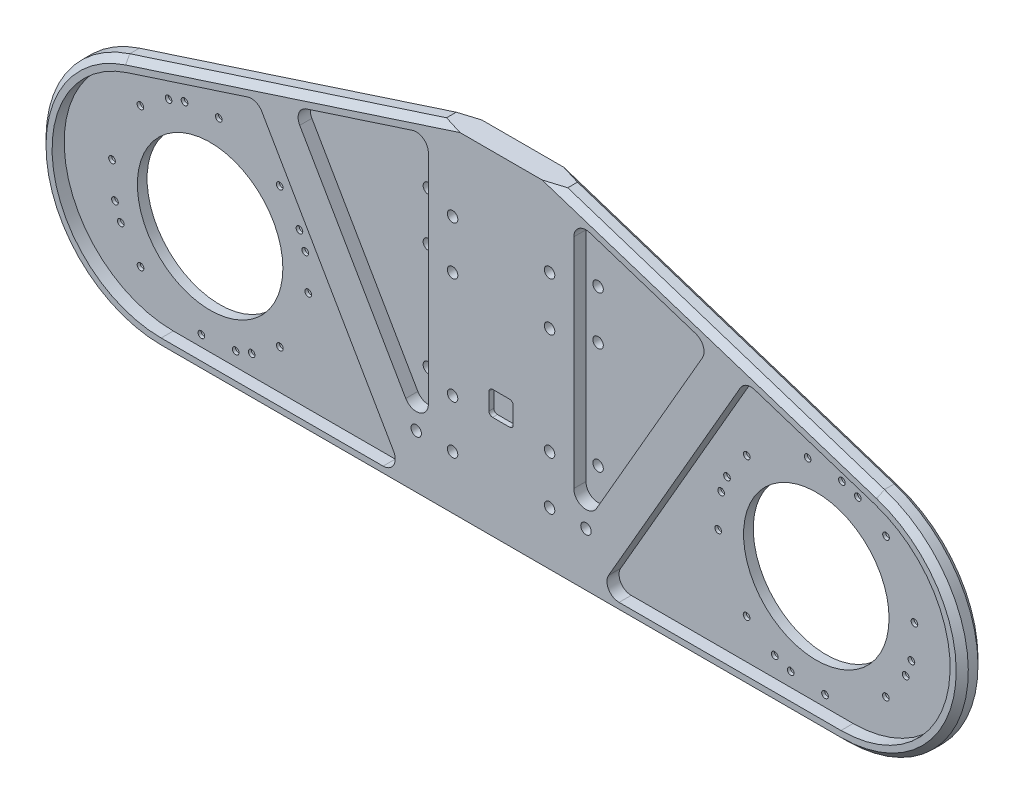
SolidWorks part; units mm, degrees
material "6061 合金"
ref_plane "前视基准面" through (0, 0, 0) normal (0, 0, 1) x (1, 0, 0)
ref_plane "上视基准面" through (0, 0, 0) normal (0, 1, 0) x (1, 0, 0)
ref_plane "右视基准面" through (0, 0, 0) normal (1, 0, 0) x (0, 0, -1)
other "Configuration Table"
sketch "草图1" plane through (0, 0, 0) normal (0, 0, 1) x (1, 0, 0)
  line L0 (0, 0) -> (0, 280) construction
  line L1 (0, 280) -> (861.7514, 0)
  line L3 (861.7514, 0) -> (0, 0)
  line L4 (-50, 352.899) -> (-50, -139.8009) construction
  line L5 (-961.7514, 0) -> (-100, 0)
  line L6 (-100, 280) -> (-961.7514, 0)
  line L7 (-100, 0) -> (-100, 280) construction
  line L8 (-100, 280) -> (0, 280)
  line L9 (0, 0) -> (-100, 0)
  circle A0 centre (200, 100) radius 85 construction
  circle A1 centre (200, 100) radius 60
  circle A2 centre (-300, 100) radius 85 construction
  circle A3 centre (-300, 100) radius 60
  dimension "D1" = 170
  dimension "D4" = 120
  dimension "D2" = 200
  dimension "D3" = 72
  dimension "D5" = 280
  dimension "D6" = 100
  dimension "D7" = 50
extrude "凸台-拉伸1" add sketch "草图1" along normal blind 8 contours L9 L3 L1 L8 L6 L5 A1 A3
fillet "圆角1" radius 100 2 edges at (861.7514, 0, 4) (-961.7514, 0, 4)
sketch "草图2" plane through (0, 0, 8) normal (0, 0, 1) x (1, 0, 0)
  line L0 (10, 266.2362) -> (10, 35.359)
  line L1 (30, 10) -> (230.3762, 10)
  line L2 (10, 266.2362) -> (122.2414, 229.7667)
  line L9 (10, 35.359) -> (122.2414, 229.7667)
  line L10 (30, 10) -> (151.4105, 220.2891)
  line L11 (151.4105, 220.2891) -> (258.1878, 185.5951)
  line L12 (10, 35.359) -> (10, 10) construction
  line L13 (10, 10) -> (30, 10) construction
  line L15 (0, 280) -> (261.2779, 195.1057) construction
  line L16 (230.3762, 0) -> (-330.3762, 0) construction
  line L19 (0, 280) -> (261.2779, 195.1057)
  line L24 (-50, 336.5114) -> (-50, -134.6936) construction
  line L29 (-100, 280) -> (0, 280) construction
  line L30 (230.3762, 0) -> (-330.3762, 0)
  line L31 (0, 280) -> (-100, 280)
  line L39 (-50, 280) -> (-50, 0)
  line L40 (-110, 10) -> (-130, 10) construction
  line L41 (-110, 35.359) -> (-110, 10) construction
  line L42 (-100, 280) -> (-361.2779, 195.1057)
  line L43 (-251.4105, 220.2891) -> (-358.1878, 185.5951)
  line L44 (-130, 10) -> (-251.4105, 220.2891)
  line L45 (-110, 35.359) -> (-222.2414, 229.7667)
  line L46 (-110, 266.2362) -> (-222.2414, 229.7667)
  line L47 (-130, 10) -> (-330.3762, 10)
  line L48 (-110, 266.2362) -> (-110, 35.359)
  arc A0 (230.3762, 10) -> (258.1878, 185.5951) centre (230.3762, 100) ccw
  arc A5 (230.3762, 0) -> (261.2779, 195.1057) centre (230.3762, 100) ccw construction
  arc A7 (230.3762, 0) -> (261.2779, 195.1057) centre (230.3762, 100) ccw
  arc A12 (-330.3762, 0) -> (-361.2779, 195.1057) centre (-330.3762, 100) cw
  arc A13 (-330.3762, 10) -> (-358.1878, 185.5951) centre (-330.3762, 100) cw
  point P33 (-50, 280)
  point P34 (-50, 0)
  line M64 (-100, 280) -> (-361.2779, 195.1057)
  arc M65 (-361.2779, 195.1057) -> (-330.3762, 0) centre (-330.3762, 100) ccw
  line M66 (-330.3762, 0) -> (230.3762, 0)
  arc M67 (230.3762, 0) -> (261.2779, 195.1057) centre (230.3762, 100) ccw
  line M68 (261.2779, 195.1057) -> (0, 280)
  line M69 (0, 280) -> (-100, 280)
  dimension "D4" = 10
  dimension "D2" = 10
  dimension "D3" = 10
  dimension "D6" = 30
  dimension "D7" = 60
  dimension "D8" = 20
  dimension "D1" = 10
extrude "凸台-拉伸2" add sketch "草图2" along normal blind 10 contours L39 L31 L46 L48 L45 L47 A13 L43 L44 M64 M65 M66 | L39 L30 A0 L1 L10 L11 L9 L0 L2 M69 M67 M68
fillet "圆角2" radius 10 10 edges at (10, 35.359, 13) (30, 10, 13) (122.2414, 229.7667, 13) (151.4105, 220.2891, 13) (10, 266.2362, 13) (-130, 10, 13) (-251.4105, 220.2891, 13) (-110, 266.2362, 13) (-222.2414, 229.7667, 13) (-110, 35.359, 13)
chamfer "倒角1" distance 5 angle 45 10 edges at (130.639, 237.5528, 0) (-50, 0, 0) (329.1451, 84.3566, 0) (-429.1451, 84.3566, 0) (-50, 0, 18) (329.1451, 84.3566, 18) (130.639, 237.5528, 18) (-230.639, 237.5528, 18) (-429.1451, 84.3566, 18) (-230.639, 237.5528, 0)
sketch "草图3" plane through (0, 0, 0) normal (0, 0, -1) x (-1, 0, 0)
  line L0 (134, 30) -> (100, 30) construction
  line L1 (-34, 236) -> (44, 236) construction
  line L2 (-34, 236) -> (-34, 158) construction
  line L3 (-34, 158) -> (44, 158) construction
  line L5 (-34, 108) -> (44, 108) construction
  line L6 (-34, 108) -> (-34, 30) construction
  line L7 (-34, 30) -> (0, 30) construction
  line L9 (134, 108) -> (134, 30) construction
  line L10 (330.3762, 0) -> (-230.3762, 0) construction
  line L11 (50, 335.2852) -> (50, -119.0767) construction
  line L12 (134, 108) -> (56, 108) construction
  line L13 (134, 158) -> (56, 158) construction
  line L14 (134, 236) -> (134, 158) construction
  line L15 (134, 236) -> (56, 236) construction
  circle A0 centre (-20, 217) radius 4.3
  circle A1 centre (-20, 177) radius 4.3
  circle A2 centre (10, 217) radius 4.3
  circle A3 centre (10, 177) radius 4.3
  circle A4 centre (-20, 89) radius 4.3
  circle A5 centre (10, 89) radius 4.3
  circle A6 centre (-20, 49) radius 4.3
  circle A7 centre (10, 49) radius 4.3
  circle A8 centre (300, 100) radius 60 construction
  circle A9 centre (-200, 100) radius 60 construction
  circle A10 centre (90, 49) radius 4.3
  circle A11 centre (120, 49) radius 4.3
  circle A12 centre (90, 89) radius 4.3
  circle A13 centre (120, 89) radius 4.3
  circle A14 centre (90, 177) radius 4.3
  circle A15 centre (90, 217) radius 4.3
  circle A16 centre (120, 177) radius 4.3
  circle A17 centre (120, 217) radius 4.3
  dimension "D7" = 8.6
  dimension "D16" = 8.6
  dimension "D1" = 78
  dimension "D2" = 78
  dimension "D3" = 30
  dimension "D4" = 78
  dimension "D5" = 30
  dimension "D6" = 50
  dimension "D8" = 19
  dimension "D9" = 19
  dimension "D10" = 19
  dimension "D11" = 19
  dimension "D12" = 14
  dimension "D13" = 14
  dimension "D14" = 40
  dimension "D17" = 19
  dimension "D18" = 19
  dimension "D19" = 19
  dimension "D20" = 19
  dimension "D21" = 14
  dimension "D22" = 14
extrude "切除-拉伸1" cut sketch "草图3" against normal through all both
sketch "草图4" plane through (0, 0, 8) normal (0, 0, 1) x (1, 0, 0)
  line L0 (-50, 330.4726) -> (-50, -61.6586) construction
  arc A0 (259.7806, 158.4465) -> (255.249, 156.3335) centre (257.5148, 157.39) ccw construction
  arc A1 (278.6673, 106.1128) -> (283.1989, 108.2258) centre (280.9331, 107.1693) ccw construction
  arc A2 (276.1928, 77.8292) -> (280.7244, 79.9423) centre (278.4586, 78.8857) ccw construction
  arc A3 (271.409, 64.6857) -> (275.9405, 66.7988) centre (273.6748, 65.7423) ccw construction
  arc A4 (255.1242, 41.4287) -> (259.6558, 43.5418) centre (257.39, 42.4852) ccw construction
  arc A5 (204.9035, 18.0104) -> (209.4351, 20.1235) centre (207.1693, 19.0669) ccw construction
  arc A6 (176.62, 20.4849) -> (181.1515, 22.598) centre (178.8857, 21.5414) ccw construction
  arc A7 (163.4765, 25.2687) -> (168.008, 27.3818) centre (165.7423, 26.3252) ccw construction
  arc A8 (140.2194, 41.5535) -> (144.751, 43.6665) centre (142.4852, 42.61) ccw construction
  arc A9 (121.3327, 93.8872) -> (116.8011, 91.7742) centre (119.0669, 92.8307) ccw construction
  arc A10 (123.8072, 122.1708) -> (119.2756, 120.0577) centre (121.5414, 121.1143) ccw construction
  arc A11 (128.591, 135.3143) -> (124.0595, 133.2012) centre (126.3252, 134.2577) ccw construction
  arc A12 (144.8758, 158.5713) -> (140.3442, 156.4582) centre (142.61, 157.5148) ccw construction
  arc A13 (195.0965, 181.9896) -> (190.5649, 179.8765) centre (192.8307, 180.9331) ccw construction
  arc A14 (223.38, 179.5151) -> (218.8485, 177.402) centre (221.1143, 178.4586) ccw construction
  arc A15 (236.5235, 174.7313) -> (231.992, 172.6182) centre (234.2577, 173.6748) ccw construction
  arc A16 (259.7806, 158.4465) -> (255.249, 156.3335) centre (257.5148, 157.39) ccw construction
  arc A17 (278.6673, 106.1128) -> (283.1989, 108.2258) centre (280.9331, 107.1693) ccw construction
  arc A18 (276.1928, 77.8292) -> (280.7244, 79.9423) centre (278.4586, 78.8857) ccw construction
  arc A19 (271.409, 64.6857) -> (275.9405, 66.7988) centre (273.6748, 65.7423) ccw construction
  arc A20 (255.1242, 41.4287) -> (259.6558, 43.5418) centre (257.39, 42.4852) ccw construction
  arc A21 (204.9035, 18.0104) -> (209.4351, 20.1235) centre (207.1693, 19.0669) ccw construction
  arc A22 (176.62, 20.4849) -> (181.1515, 22.598) centre (178.8857, 21.5414) ccw construction
  arc A23 (163.4765, 25.2687) -> (168.008, 27.3818) centre (165.7423, 26.3252) ccw construction
  arc A24 (140.2194, 41.5535) -> (144.751, 43.6665) centre (142.4852, 42.61) ccw construction
  arc A25 (121.3327, 93.8872) -> (116.8011, 91.7742) centre (119.0669, 92.8307) ccw construction
  arc A26 (123.8072, 122.1708) -> (119.2756, 120.0577) centre (121.5414, 121.1143) ccw construction
  arc A27 (128.591, 135.3143) -> (124.0595, 133.2012) centre (126.3252, 134.2577) ccw construction
  arc A28 (144.8758, 158.5713) -> (140.3442, 156.4582) centre (142.61, 157.5148) ccw construction
  arc A29 (195.0965, 181.9896) -> (190.5649, 179.8765) centre (192.8307, 180.9331) ccw construction
  arc A30 (223.38, 179.5151) -> (218.8485, 177.402) centre (221.1143, 178.4586) ccw construction
  arc A31 (236.5235, 174.7313) -> (231.992, 172.6182) centre (234.2577, 173.6748) ccw construction
  circle A32 centre (257.5148, 157.39) radius 2.75
  circle A33 centre (234.2577, 173.6748) radius 2.75
  circle A34 centre (221.1143, 178.4586) radius 2.75
  circle A35 centre (192.8307, 180.9331) radius 2.75
  circle A36 centre (142.61, 157.5148) radius 2.75
  circle A37 centre (126.3252, 134.2577) radius 2.75
  circle A38 centre (121.5414, 121.1143) radius 2.75
  circle A39 centre (119.0669, 92.8307) radius 2.75
  circle A40 centre (142.4852, 42.61) radius 2.75
  circle A41 centre (165.7423, 26.3252) radius 2.75
  circle A42 centre (178.8857, 21.5414) radius 2.75
  circle A43 centre (207.1693, 19.0669) radius 2.75
  circle A44 centre (257.39, 42.4852) radius 2.75
  circle A45 centre (273.6748, 65.7423) radius 2.75
  circle A46 centre (278.4586, 78.8857) radius 2.75
  circle A47 centre (280.9331, 107.1693) radius 2.75
  circle A48 centre (200, 100) radius 60 construction
  circle A49 centre (-300, 100) radius 60 construction
  arc A50 (-336.5235, 174.7313) -> (-331.992, 172.6182) centre (-334.2577, 173.6748) cw construction
  arc A51 (-323.38, 179.5151) -> (-318.8485, 177.402) centre (-321.1143, 178.4586) cw construction
  arc A52 (-295.0965, 181.9896) -> (-290.5649, 179.8765) centre (-292.8307, 180.9331) cw construction
  arc A53 (-244.8758, 158.5713) -> (-240.3442, 156.4582) centre (-242.61, 157.5148) cw construction
  arc A54 (-228.591, 135.3143) -> (-224.0595, 133.2012) centre (-226.3252, 134.2577) cw construction
  arc A55 (-223.8072, 122.1708) -> (-219.2756, 120.0577) centre (-221.5414, 121.1143) cw construction
  arc A56 (-221.3327, 93.8872) -> (-216.8011, 91.7742) centre (-219.0669, 92.8307) cw construction
  arc A57 (-240.2194, 41.5535) -> (-244.751, 43.6665) centre (-242.4852, 42.61) cw construction
  arc A58 (-263.4765, 25.2687) -> (-268.008, 27.3818) centre (-265.7423, 26.3252) cw construction
  arc A59 (-276.62, 20.4849) -> (-281.1515, 22.598) centre (-278.8857, 21.5414) cw construction
  arc A60 (-304.9035, 18.0104) -> (-309.4351, 20.1235) centre (-307.1693, 19.0669) cw construction
  arc A61 (-355.1242, 41.4287) -> (-359.6558, 43.5418) centre (-357.39, 42.4852) cw construction
  arc A62 (-371.409, 64.6857) -> (-375.9405, 66.7988) centre (-373.6748, 65.7423) cw construction
  arc A63 (-376.1928, 77.8292) -> (-380.7244, 79.9423) centre (-378.4586, 78.8857) cw construction
  arc A64 (-378.6673, 106.1128) -> (-383.1989, 108.2258) centre (-380.9331, 107.1693) cw construction
  arc A65 (-359.7806, 158.4465) -> (-355.249, 156.3335) centre (-357.5148, 157.39) cw construction
  circle A66 centre (-380.9331, 107.1693) radius 2.75
  circle A67 centre (-378.4586, 78.8857) radius 2.75
  circle A68 centre (-373.6748, 65.7423) radius 2.75
  circle A69 centre (-357.39, 42.4852) radius 2.75
  circle A70 centre (-307.1693, 19.0669) radius 2.75
  circle A71 centre (-278.8857, 21.5414) radius 2.75
  circle A72 centre (-265.7423, 26.3252) radius 2.75
  circle A73 centre (-242.4852, 42.61) radius 2.75
  circle A74 centre (-219.0669, 92.8307) radius 2.75
  circle A75 centre (-221.5414, 121.1143) radius 2.75
  circle A76 centre (-226.3252, 134.2577) radius 2.75
  circle A77 centre (-242.61, 157.5148) radius 2.75
  circle A78 centre (-292.8307, 180.9331) radius 2.75
  circle A79 centre (-321.1143, 178.4586) radius 2.75
  circle A80 centre (-334.2577, 173.6748) radius 2.75
  circle A81 centre (-357.5148, 157.39) radius 2.75
  dimension "D1" = 5.5
extrude "切除-拉伸2" cut sketch "草图4" against normal blind 10 contours A44 | A45 | A46 | A47 | A32 | A33 | A34 | A35 | A36 | A37 | A38 | A39 | A40 | A41 | A42 | A73 | A72 | A71 | A70 | A69 | A68 | A67 | A66 | A81 | A80 | A79 | A78 | A77 | A76 | A75 | A74 | A43
sketch "草图5" plane through (0, 0, 0) normal (0, 0, -1) x (-1, 0, 0)
  line L0 (50, 354.5789) -> (50, -118.9875) construction
  circle A0 centre (-192.8307, 180.9331) radius 6
  circle A1 centre (-142.61, 157.5148) radius 6
  circle A2 centre (-126.3252, 134.2577) radius 6
  circle A3 centre (-121.5414, 121.1143) radius 6
  circle A4 centre (-119.0669, 92.8307) radius 6
  circle A5 centre (-142.4852, 42.61) radius 6
  circle A6 centre (-165.7423, 26.3252) radius 6
  circle A7 centre (-178.8857, 21.5414) radius 6
  circle A8 centre (-207.1693, 19.0669) radius 6
  circle A9 centre (-257.39, 42.4852) radius 6
  circle A10 centre (-273.6748, 65.7423) radius 6
  circle A11 centre (-278.4586, 78.8857) radius 6
  circle A12 centre (-280.9331, 107.1693) radius 6
  circle A13 centre (-257.5148, 157.39) radius 6
  circle A14 centre (-234.2577, 173.6748) radius 6
  circle A15 centre (-221.1143, 178.4586) radius 6
  circle A16 centre (300, 100) radius 60 construction
  circle A17 centre (-200, 100) radius 60 construction
  circle A18 centre (321.1143, 178.4586) radius 6
  circle A19 centre (334.2577, 173.6748) radius 6
  circle A20 centre (357.5148, 157.39) radius 6
  circle A21 centre (380.9331, 107.1693) radius 6
  circle A22 centre (378.4586, 78.8857) radius 6
  circle A23 centre (373.6748, 65.7423) radius 6
  circle A24 centre (357.39, 42.4852) radius 6
  circle A25 centre (307.1693, 19.0669) radius 6
  circle A26 centre (278.8857, 21.5414) radius 6
  circle A27 centre (265.7423, 26.3252) radius 6
  circle A28 centre (242.4852, 42.61) radius 6
  circle A29 centre (219.0669, 92.8307) radius 6
  circle A30 centre (221.5414, 121.1143) radius 6
  circle A31 centre (226.3252, 134.2577) radius 6
  circle A32 centre (242.61, 157.5148) radius 6
  circle A33 centre (292.8307, 180.9331) radius 6
  dimension "D1" = 12
extrude "切除-拉伸3" cut sketch "草图5" against normal blind 5.5
sketch "草图6" plane through (0, 0, 18) normal (0, 0, 1) x (1, 0, 0)
  line L0 (-50, 324.4003) -> (-50, -115.846) construction
  line L1 (-300, 100) -> (200, 100) construction
  line L3 (-60, 110) -> (-40, 110)
  line L4 (-60, 110) -> (-60, 90)
  line L5 (-60, 90) -> (-40, 90)
  line L6 (-40, 110) -> (-40, 90)
  circle A0 centre (200, 100) radius 60 construction
  circle A1 centre (-300, 100) radius 60 construction
  dimension "D1" = 20
  dimension "D2" = 20
extrude "切除-拉伸4" cut sketch "草图6" against normal blind 4
fillet "圆角3" radius 3 4 edges at (-40, 90, 16) (-60, 90, 16) (-60, 110, 16) (-40, 110, 16)
